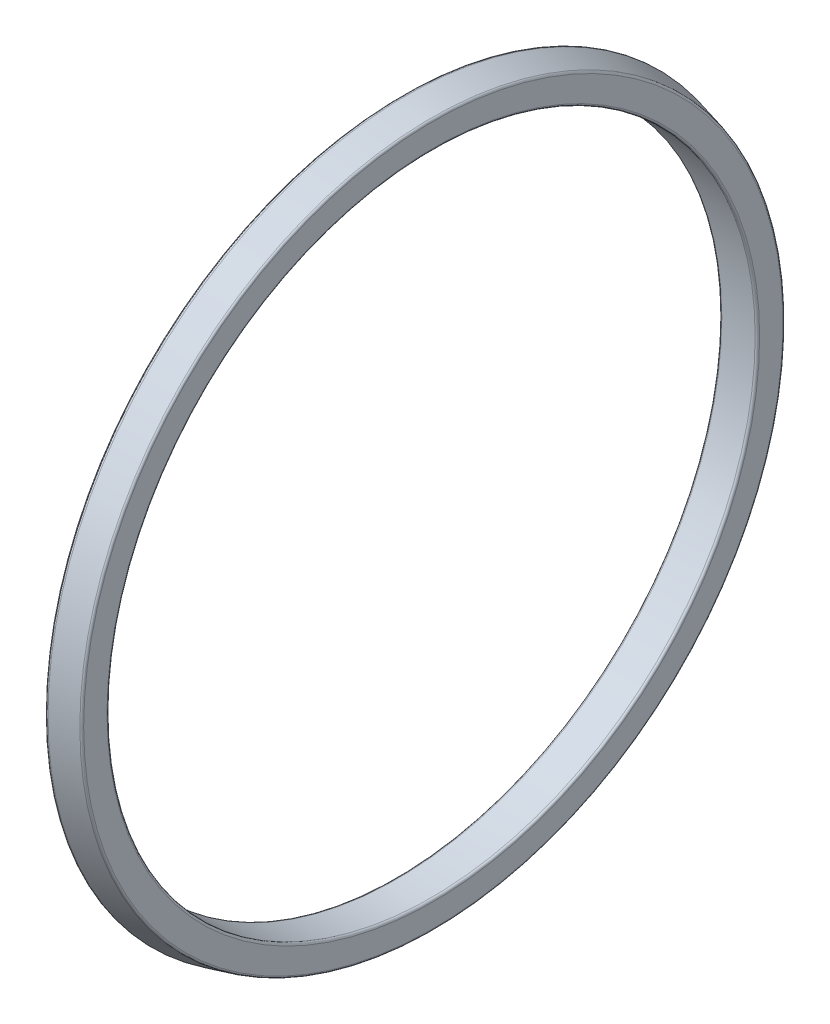
SolidWorks part; units mm, degrees
ref_plane "Alzado" through (0, 0, 0) normal (0, 0, 1) x (1, 0, 0)
ref_plane "Planta" through (0, 0, 0) normal (0, 1, 0) x (1, 0, 0)
ref_plane "Vista lateral" through (0, 0, 0) normal (1, 0, 0) x (0, 0, -1)
sketch "Croquis1" plane through (0, 0, 0) normal (0, 1, 0) x (1, 0, 0)
  line L0 (0, 0) -> (0, 16) construction
  line L1 (201.3018, 380.8705) -> (1111.9685, 380.8705) construction
  line L2 (0.551, 14.4238) -> (2.0334, 14.4238)
  line L3 (2.1334, 14.5238) -> (2.1334, 15.5605)
  line L4 (2.0583, 15.6574) -> (0.9294, 15.9474)
  line L5 (0.8321, 15.9196) -> (0.7263, 15.8086)
  line L6 (0.7508, 15.6518) -> (1.3691, 15.3145)
  line L7 (1.3317, 15.1273) -> (0.5405, 15.0437)
  line L8 (0.451, 14.9442) -> (0.451, 14.5238)
  line L9 (0, 0) -> (15.706, 0) construction
  arc A0 (2.1334, 14.5238) -> (2.0334, 14.4238) centre (2.0334, 14.5238) cw
  arc A1 (0.551, 14.4238) -> (0.451, 14.5238) centre (0.551, 14.5238) cw
  arc A2 (0.5405, 15.0437) -> (0.451, 14.9442) centre (0.551, 14.9442) ccw
  arc A3 (1.3317, 15.1273) -> (1.3691, 15.3145) centre (1.3212, 15.2267) ccw
  arc A4 (0.7263, 15.8086) -> (0.7508, 15.6518) centre (0.7987, 15.7396) ccw
  arc A5 (0.8321, 15.9196) -> (0.9294, 15.9474) centre (0.9045, 15.8505) cw
  arc A6 (2.1334, 15.5605) -> (2.0583, 15.6574) centre (2.0334, 15.5605) ccw
  dimension "D2" = 0.1
  dimension "D1" = 16
revolve "Revolución1" add sketch "Croquis1" angle 360 about L9
